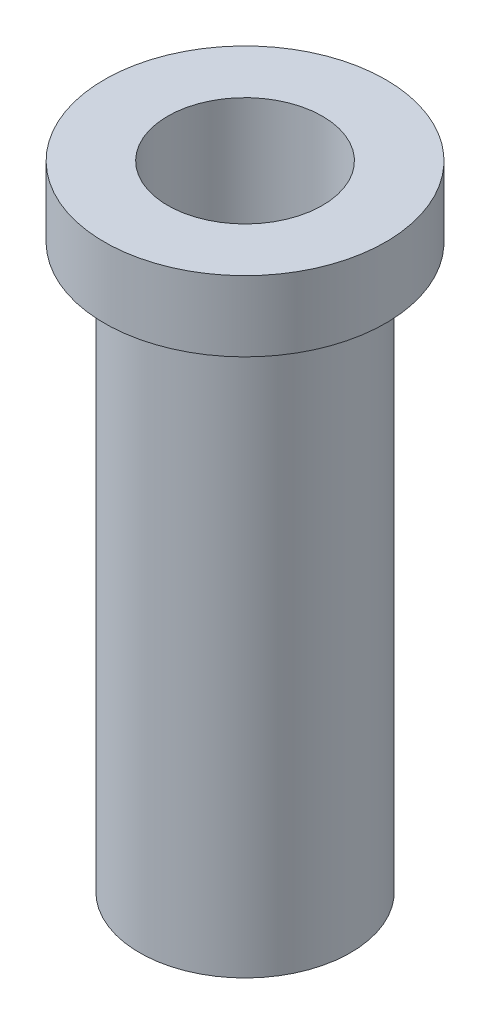
SolidWorks part; units mm, degrees
ref_plane "Front Plane" through (0, 0, 0) normal (0, 0, 1) x (1, 0, 0)
ref_plane "Top Plane" through (0, 0, 0) normal (0, 1, 0) x (1, 0, 0)
ref_plane "Right Plane" through (0, 0, 0) normal (1, 0, 0) x (0, 0, -1)
sketch "Sketch1" plane through (0, 0, 0) normal (0, 0, 1) x (1, 0, 0)
  line L0 (5.5, 0) -> (5.5, 45)
  line L1 (5.5, 45) -> (10, 45)
  line L2 (10, 45) -> (10, 40)
  line L3 (10, 40) -> (7.5, 40)
  line L4 (7.5, 40) -> (7.5, 0)
  line L5 (7.5, 0) -> (5.5, 0)
  line L6 (0, 0) -> (0, 58.7326) construction
  dimension "D1" = 5
  dimension "D2" = 5.5
  dimension "D3" = 7.5
  dimension "D4" = 10
  dimension "D5" = 40
revolve "Revolve1" add sketch "Sketch1" angle 360 about L6
